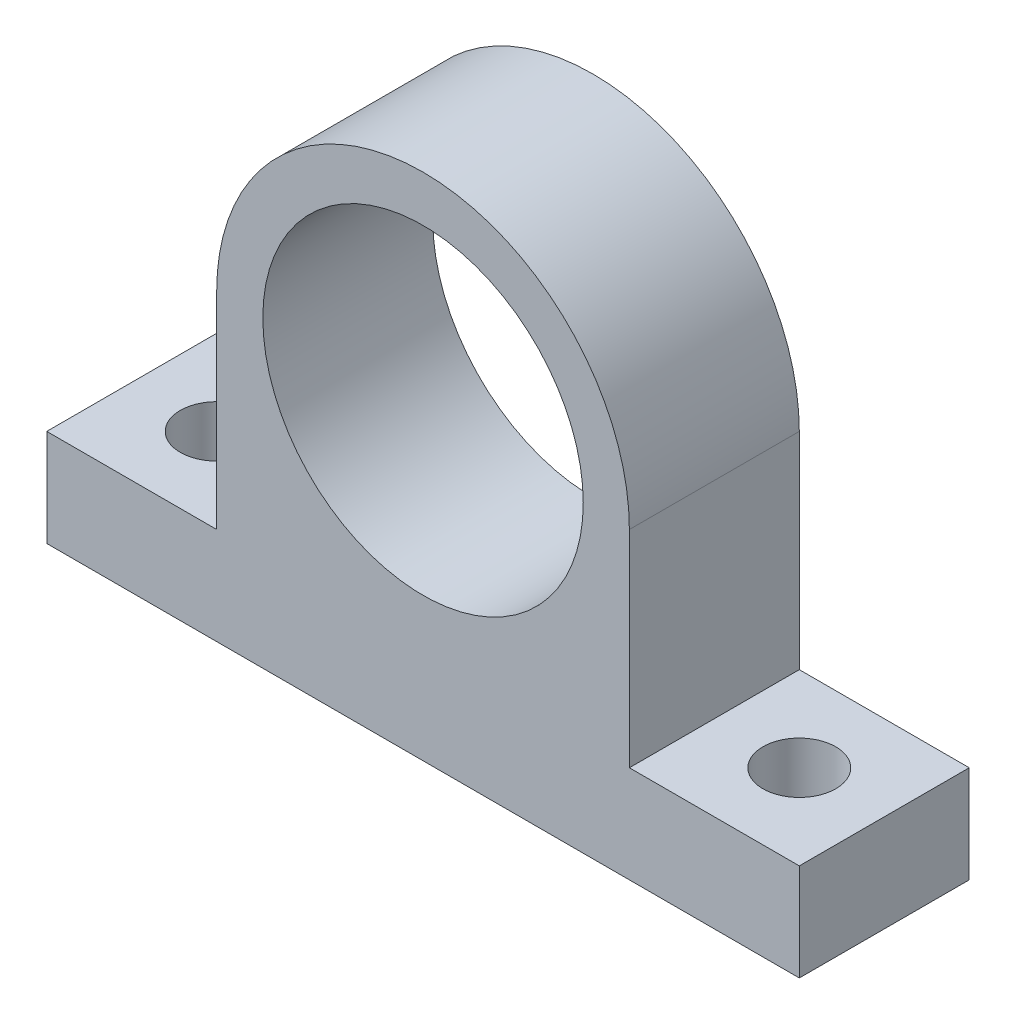
SolidWorks part; units mm, degrees
ref_plane "前视基准面" through (0, 0, 0) normal (0, 0, 1) x (1, 0, 0)
ref_plane "上视基准面" through (0, 0, 0) normal (0, 1, 0) x (1, 0, 0)
ref_plane "右视基准面" through (0, 0, 0) normal (1, 0, 0) x (0, 0, -1)
sketch "草图1" plane through (0, 0, 0) normal (0, 0, 1) x (1, 0, 0)
  line L0 (0, -8.5) -> (0, -12.5) construction
  line L1 (-8.5, 0) -> (-8.5, -8.5)
  line L2 (8.5, 0) -> (8.5, -8.5)
  line L4 (8.5, -8.5) -> (15.5, -8.5)
  line L5 (15.5, -8.5) -> (15.5, -12.5)
  line L6 (15.5, -12.5) -> (8.5, -12.5)
  line L7 (-8.5, -8.5) -> (-15.5, -8.5)
  line L8 (-15.5, -8.5) -> (-15.5, -12.5)
  line L9 (-15.5, -12.5) -> (-8.5, -12.5)
  line L10 (-8.5, -12.5) -> (8.5, -12.5)
  circle A0 centre (0, 0) radius 6.6
  arc A1 (8.5, 0) -> (-8.5, 0) centre (0, 0) ccw
  point P12 (0, -8.5)
  dimension "D1" = 13.2
  dimension "D2" = 17
  dimension "D3" = 4
  dimension "D4" = 7
  dimension "D5" = 7
extrude "凸台-拉伸1" add sketch "草图1" along normal blind 7
sketch "草图2" plane through (0, -8.5, 0) normal (0, 1, 0) x (1, 0, 0)
  line L0 (-12, 0) -> (-12, -7) construction
  line L1 (-8.5, 0) -> (-15.5, 0) construction
  line L2 (-8.5, -7) -> (-15.5, -7) construction
  line L3 (0, 0) -> (0, -7) construction
  line L4 (-8.5, -7) -> (8.5, -7) construction
  circle A0 centre (-12, -3.5) radius 1.5
  circle A1 centre (12, -3.5) radius 1.5
  dimension "D1" = 3
extrude "切除-拉伸1" cut sketch "草图2" against normal through all
